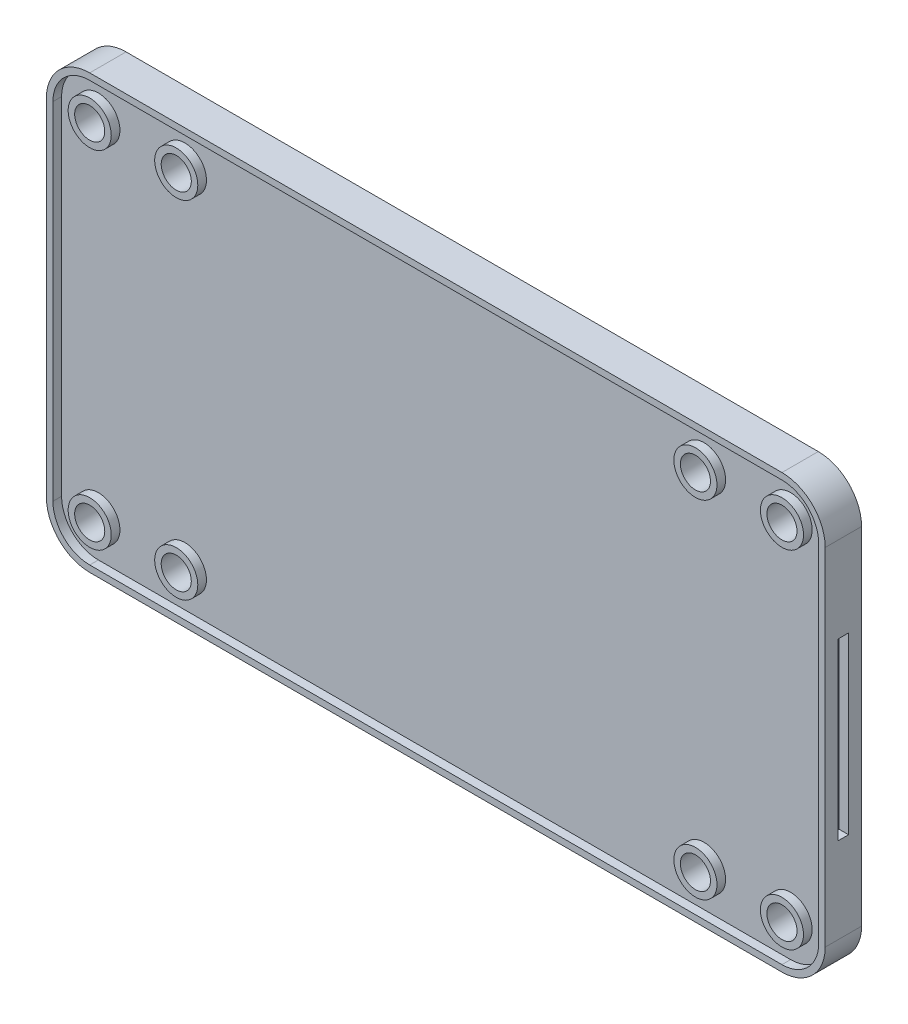
SolidWorks part; units mm, degrees
material "ABS"
ref_plane "Front Plane" through (0, 0, 0) normal (0, 0, 1) x (1, 0, 0)
ref_plane "Top Plane" through (0, 0, 0) normal (0, 1, 0) x (1, 0, 0)
ref_plane "Right Plane" through (0, 0, 0) normal (1, 0, 0) x (0, 0, -1)
sketch "Sketch1" plane through (0, 0, 0) normal (0, 0, 1) x (1, 0, 0)
  line L0 (-57.15, 0) -> (57.15, 0) construction
  line L1 (-50.8, -31.75) -> (50.8, -31.75)
  line L2 (-57.15, -25.4) -> (-57.15, 25.4)
  line L3 (-50.8, 31.75) -> (50.8, 31.75)
  line L4 (57.15, -25.4) -> (57.15, 25.4)
  line L5 (-57.15, -31.75) -> (57.15, 31.75) construction
  line L6 (-57.15, 31.75) -> (57.15, -31.75) construction
  line L7 (0, 31.75) -> (0, -31.75) construction
  arc A0 (50.8, 31.75) -> (57.15, 25.4) centre (50.8, 25.4) cw
  arc A1 (50.8, -31.75) -> (57.15, -25.4) centre (50.8, -25.4) ccw
  arc A2 (-50.8, -31.75) -> (-57.15, -25.4) centre (-50.8, -25.4) cw
  arc A3 (-57.15, 25.4) -> (-50.8, 31.75) centre (-50.8, 25.4) cw
  circle A4 centre (-50.8, -25.4) radius 2.2098
  circle A5 centre (-38.1, -25.4) radius 2.2098
  circle A6 centre (-50.8, 25.4) radius 2.2098
  circle A7 centre (-38.1, 25.4) radius 2.2098
  circle A8 centre (50.8, 25.4) radius 2.2098
  circle A9 centre (38.1, 25.4) radius 2.2098
  circle A10 centre (50.8, -25.4) radius 2.2098
  circle A11 centre (38.1, -25.4) radius 2.2098
  point P0 (0, 0)
  dimension "D3" = 6.35
  dimension "D4" = 4.4196
  dimension "D1" = 63.5
  dimension "D2" = 114.3
  dimension "D5" = 6.35
  dimension "D6" = 12.7
  dimension "D7" = 6.35
extrude "Boss-Extrude1" add sketch "Sketch1" against normal blind 3.175
sketch "Sketch2" plane through (0, 0, 0) normal (0, 0, 1) x (1, 0, 0)
  line L12 (50.8, 30.7975) -> (-50.8, 30.7975)
  line L13 (-56.1975, 25.4) -> (-56.1975, -25.4)
  line L14 (-50.8, -30.7975) -> (50.8, -30.7975)
  line L15 (56.1975, -25.4) -> (56.1975, 25.4)
  line L16 (50.8, 30.7975) -> (-50.8, 30.7975)
  line L17 (-56.1975, 25.4) -> (-56.1975, -25.4)
  line L18 (-50.8, -30.7975) -> (50.8, -30.7975)
  line L19 (56.1975, -25.4) -> (56.1975, 25.4)
  circle A0 centre (-50.8, -25.4) radius 2.2098 construction
  arc A8 (56.1975, 25.4) -> (50.8, 30.7975) centre (50.8, 25.4) ccw
  arc A9 (-50.8, 30.7975) -> (-56.1975, 25.4) centre (-50.8, 25.4) ccw
  arc A10 (-56.1975, -25.4) -> (-50.8, -30.7975) centre (-50.8, -25.4) ccw
  arc A11 (50.8, -30.7975) -> (56.1975, -25.4) centre (50.8, -25.4) ccw
  arc A12 (56.1975, 25.4) -> (50.8, 30.7975) centre (50.8, 25.4) ccw
  arc A13 (-50.8, 30.7975) -> (-56.1975, 25.4) centre (-50.8, 25.4) ccw
  arc A14 (-56.1975, -25.4) -> (-50.8, -30.7975) centre (-50.8, -25.4) ccw
  arc A15 (50.8, -30.7975) -> (56.1975, -25.4) centre (50.8, -25.4) ccw
  circle A36 centre (38.1, 25.4) radius 3.1623
  circle A37 centre (50.8, 25.4) radius 3.1623
  circle A38 centre (50.8, -25.4) radius 3.1623
  circle A39 centre (38.1, -25.4) radius 3.1623
  circle A40 centre (-38.1, -25.4) radius 3.1623
  circle A41 centre (-50.8, -25.4) radius 3.1623
  circle A42 centre (-38.1, 25.4) radius 3.1623
  circle A43 centre (-50.8, 25.4) radius 3.1623
  circle A44 centre (-38.1, -25.4) radius 2.2098 construction
  circle A47 centre (38.1, -25.4) radius 2.2098 construction
  circle A50 centre (50.8, -25.4) radius 2.2098 construction
  circle A51 centre (50.8, 25.4) radius 2.2098 construction
  circle A52 centre (38.1, 25.4) radius 2.2098 construction
  circle A53 centre (-38.1, 25.4) radius 2.2098 construction
  circle A54 centre (-50.8, 25.4) radius 2.2098 construction
  dimension "D2" = 0.9525
  dimension "D1" = 0.9525
extrude "Cut-Extrude3" cut sketch "Sketch2" against normal blind 1.27
sketch "Sketch3" plane through (0, 0, -3.175) normal (0, 0, -1) x (-1, 0, 0)
  line L4 (-57.15, 25.4) -> (-57.15, -25.4)
  line L5 (-50.8, -31.75) -> (50.8, -31.75)
  line L6 (57.15, -25.4) -> (57.15, 25.4)
  line L7 (50.8, 31.75) -> (-50.8, 31.75)
  line L8 (-57.15, 25.4) -> (-57.15, -25.4)
  line L9 (-50.8, -31.75) -> (50.8, -31.75)
  line L10 (57.15, -25.4) -> (57.15, 25.4)
  line L11 (50.8, 31.75) -> (-50.8, 31.75)
  circle A0 centre (-50.8, -25.4) radius 2.2098 construction
  circle A1 centre (-38.1, -25.4) radius 2.2098 construction
  circle A2 centre (38.1, -25.4) radius 2.2098 construction
  circle A3 centre (50.8, -25.4) radius 2.2098 construction
  arc A4 (-50.8, 31.75) -> (-57.15, 25.4) centre (-50.8, 25.4) ccw
  arc A5 (-57.15, -25.4) -> (-50.8, -31.75) centre (-50.8, -25.4) ccw
  arc A6 (50.8, -31.75) -> (57.15, -25.4) centre (50.8, -25.4) ccw
  arc A7 (57.15, 25.4) -> (50.8, 31.75) centre (50.8, 25.4) ccw
  arc A8 (-50.8, 31.75) -> (-57.15, 25.4) centre (-50.8, 25.4) ccw
  arc A9 (-57.15, -25.4) -> (-50.8, -31.75) centre (-50.8, -25.4) ccw
  arc A10 (50.8, -31.75) -> (57.15, -25.4) centre (50.8, -25.4) ccw
  arc A11 (57.15, 25.4) -> (50.8, 31.75) centre (50.8, 25.4) ccw
  circle A12 centre (50.8, 25.4) radius 2.2098 construction
  circle A13 centre (38.1, 25.4) radius 2.2098 construction
  circle A14 centre (-38.1, 25.4) radius 2.2098 construction
  circle A15 centre (-50.8, 25.4) radius 2.2098 construction
  circle A16 centre (-50.8, -25.4) radius 2.2098
  circle A17 centre (-38.1, -25.4) radius 2.2098
  circle A18 centre (38.1, -25.4) radius 2.2098
  circle A19 centre (50.8, -25.4) radius 2.2098
  circle A20 centre (50.8, 25.4) radius 2.2098
  circle A21 centre (38.1, 25.4) radius 2.2098
  circle A22 centre (-38.1, 25.4) radius 2.2098
  circle A23 centre (-50.8, 25.4) radius 2.2098
  dimension "D1" = 0
extrude "Boss-Extrude2" add sketch "Sketch3" along normal blind 2.159
sketch "Sketch4" plane through (57.15, 0, 0) normal (1, 0, 0) x (0, 0, -1)
  line L0 (5.334, -25.4) -> (0, -25.4) construction
  line L1 (1.905, 12.827) -> (3.429, 12.827)
  line L2 (1.905, 12.827) -> (1.905, -12.827)
  line L3 (1.905, -12.827) -> (3.429, -12.827)
  line L4 (3.429, 12.827) -> (3.429, -12.827)
  point P6 (2.667, -25.4)
  point P7 (2.667, -12.827)
  point P8 (1.905, 0)
  dimension "D1" = 1.524
  dimension "D2" = 25.654
extrude "Cut-Extrude4" cut sketch "Sketch4" against normal blind 1.397
mirror "Mirror1" about plane through (0, 0, 0) normal (1, 0, 0) of "Cut-Extrude4"
sketch "Sketch5" plane through (0, 0, -5.334) normal (0, 0, -1) x (-1, 0, 0)
  circle A0 centre (0, 0) radius 12.7
  dimension "D1" = 25.4
extrude "Cut-Extrude5" cut sketch "Sketch5" against normal blind 2.54
equation "\"tolerance\"= 0.005"
equation "\"D4@Sketch1\"=0.164 + \"tolerance\" * 2"
equation "\"D1@Boss-Extrude2\"= 0.080000in + \"tolerance\""
equation "\"D1@Sketch4\" = 0.05 + \"tolerance\" * 2"
equation "\"D2@Sketch4\" = 1 + \"tolerance\" * 2"
equation "\"D1@Cut-Extrude4\"= 0.05 + \"tolerance\""
